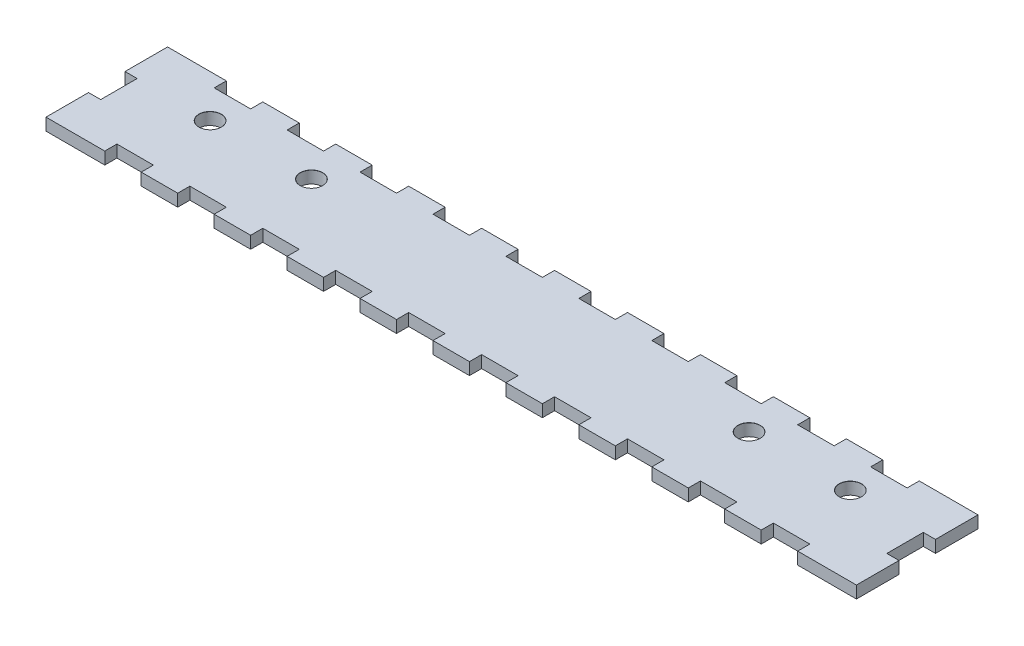
SolidWorks part; units mm, degrees
ref_plane "Front Plane" through (0, 0, 0) normal (0, 0, 1) x (1, 0, 0)
ref_plane "Top Plane" through (0, 0, 0) normal (0, 1, 0) x (1, 0, 0)
ref_plane "Right Plane" through (0, 0, 0) normal (1, 0, 0) x (0, 0, -1)
sketch "Sketch1" plane through (0, 0, 0) normal (0, 1, 0) x (1, 0, 0)
  line L0 (100, 15) -> (97, 15)
  line L1 (97, 15) -> (85.5, 15)
  line L2 (85.5, 15) -> (85.5, 12)
  line L3 (85.5, 12) -> (76.5, 12)
  line L4 (76.5, 12) -> (76.5, 15)
  line L5 (76.5, 15) -> (67.5, 15)
  line L6 (67.5, 15) -> (67.5, 12)
  line L7 (67.5, 12) -> (58.5, 12)
  line L8 (58.5, 12) -> (58.5, 15)
  line L9 (58.5, 15) -> (49.5, 15)
  line L10 (49.5, 15) -> (49.5, 12)
  line L11 (49.5, 12) -> (40.5, 12)
  line L12 (40.5, 12) -> (40.5, 15)
  line L13 (40.5, 15) -> (31.5, 15)
  line L14 (31.5, 15) -> (31.5, 12)
  line L15 (31.5, 12) -> (22.5, 12)
  line L16 (22.5, 12) -> (22.5, 15)
  line L17 (22.5, 15) -> (13.5, 15)
  line L18 (13.5, 15) -> (13.5, 12)
  line L19 (13.5, 12) -> (4.5, 12)
  line L20 (4.5, 12) -> (4.5, 15)
  line L21 (4.5, 15) -> (-4.5, 15)
  line L22 (-4.5, 15) -> (-4.5, 12)
  line L23 (-4.5, 12) -> (-13.5, 12)
  line L24 (-13.5, 12) -> (-13.5, 15)
  line L25 (-13.5, 15) -> (-22.5, 15)
  line L26 (-22.5, 15) -> (-22.5, 12)
  line L27 (-22.5, 12) -> (-31.5, 12)
  line L28 (-31.5, 12) -> (-31.5, 15)
  line L29 (-31.5, 15) -> (-40.5, 15)
  line L30 (-40.5, 15) -> (-40.5, 12)
  line L31 (-40.5, 12) -> (-49.5, 12)
  line L32 (-49.5, 12) -> (-49.5, 15)
  line L33 (-49.5, 15) -> (-58.5, 15)
  line L34 (-58.5, 15) -> (-58.5, 12)
  line L35 (-58.5, 12) -> (-67.5, 12)
  line L36 (-67.5, 12) -> (-67.5, 15)
  line L37 (-67.5, 15) -> (-76.5, 15)
  line L38 (-76.5, 15) -> (-76.5, 12)
  line L39 (-76.5, 12) -> (-85.5, 12)
  line L40 (-85.5, 12) -> (-85.5, 15)
  line L41 (-85.5, 15) -> (-97, 15)
  line L42 (-97, 15) -> (-100, 15)
  line L43 (-100, 15) -> (-100, 12)
  line L44 (-100, 12) -> (-100, 4.5)
  line L45 (-100, 4.5) -> (-97, 4.5)
  line L46 (-97, 4.5) -> (-97, -4.5)
  line L47 (-97, -4.5) -> (-100, -4.5)
  line L48 (-100, -4.5) -> (-100, -12)
  line L49 (-100, -12) -> (-100, -15)
  line L50 (-100, -15) -> (-97, -15)
  line L51 (-97, -15) -> (-85.5, -15)
  line L52 (-85.5, -15) -> (-85.5, -12)
  line L53 (-85.5, -12) -> (-76.5, -12)
  line L54 (-76.5, -12) -> (-76.5, -15)
  line L55 (-76.5, -15) -> (-67.5, -15)
  line L56 (-67.5, -15) -> (-67.5, -12)
  line L57 (-67.5, -12) -> (-58.5, -12)
  line L58 (-58.5, -12) -> (-58.5, -15)
  line L59 (-58.5, -15) -> (-49.5, -15)
  line L60 (-49.5, -15) -> (-49.5, -12)
  line L61 (-49.5, -12) -> (-40.5, -12)
  line L62 (-40.5, -12) -> (-40.5, -15)
  line L63 (-40.5, -15) -> (-31.5, -15)
  line L64 (-31.5, -15) -> (-31.5, -12)
  line L65 (-31.5, -12) -> (-22.5, -12)
  line L66 (-22.5, -12) -> (-22.5, -15)
  line L67 (-22.5, -15) -> (-13.5, -15)
  line L68 (-13.5, -15) -> (-13.5, -12)
  line L69 (-13.5, -12) -> (-4.5, -12)
  line L70 (-4.5, -12) -> (-4.5, -15)
  line L71 (-4.5, -15) -> (4.5, -15)
  line L72 (4.5, -15) -> (4.5, -12)
  line L73 (4.5, -12) -> (13.5, -12)
  line L74 (13.5, -12) -> (13.5, -15)
  line L75 (13.5, -15) -> (22.5, -15)
  line L76 (22.5, -15) -> (22.5, -12)
  line L77 (22.5, -12) -> (31.5, -12)
  line L78 (31.5, -12) -> (31.5, -15)
  line L79 (31.5, -15) -> (40.5, -15)
  line L80 (40.5, -15) -> (40.5, -12)
  line L81 (40.5, -12) -> (49.5, -12)
  line L82 (49.5, -12) -> (49.5, -15)
  line L83 (49.5, -15) -> (58.5, -15)
  line L84 (58.5, -15) -> (58.5, -12)
  line L85 (58.5, -12) -> (67.5, -12)
  line L86 (67.5, -12) -> (67.5, -15)
  line L87 (67.5, -15) -> (76.5, -15)
  line L88 (76.5, -15) -> (76.5, -12)
  line L89 (76.5, -12) -> (85.5, -12)
  line L90 (85.5, -12) -> (85.5, -15)
  line L91 (85.5, -15) -> (97, -15)
  line L92 (97, -15) -> (100, -15)
  line L93 (100, -15) -> (100, -12)
  line L94 (100, -12) -> (100, -4.5)
  line L95 (100, -4.5) -> (97, -4.5)
  line L96 (97, -4.5) -> (97, 4.5)
  line L97 (97, 4.5) -> (100, 4.5)
  line L98 (100, 4.5) -> (100, 12)
  line L99 (100, 12) -> (100, 15)
  line L100 (-100, 15) -> (100, -15) construction
  point P100 (0, 0)
extrude "Boss-Extrude1" add sketch "Sketch1" along normal mid plane 3
sketch "Sketch2" plane through (0, 1.5, 0) normal (0, 1, 0) x (1, 0, 0)
  text T0 "Left/Right\r\n"
extrude "Cut-Extrude1" [suppressed] cut sketch "Sketch2" against normal blind 1
sketch "Sketch3" plane through (0, 1.5, 0) normal (0, 1, 0) x (1, 0, 0)
  line L0 (0, 41.8956) -> (0, -48.2972) construction
  line L1 (-79, 4.5) -> (-54, 4.5) construction
  line L2 (-100, 15) -> (-100, 4.5) construction
  line L3 (-67.5, 15) -> (-76.5, 15) construction
  line L4 (79, 4.5) -> (54, 4.5) construction
  point P3 (-79, 4.5)
  point P4 (-54, 4.5)
  point P9 (79, 4.5)
  point P10 (54, 4.5)
  dimension "D1" = 25
  dimension "D2" = 21
  dimension "D3" = 10.5
hole_wizard "M5 Clearance Hole1" positions "Sketch3" profile "Sketch4" hole size "M5" standard "ISO" end condition through all
sketch "Sketch4" plane through (54, 1.5, -4.5) normal (1, 0, 0) x (0, 0, 1)
  line L0 (0, 0) -> (0, 3)
  line L1 (0, 3) -> (2.75, 3)
  line L2 (2.75, 3) -> (2.75, 0.025)
  line L3 (2.75, 0.025) -> (2.775, 0)
  line L5 (2.775, 0) -> (0, 0)
  line L6 (-2.75, 0.025) -> (-2.775, 0) construction
  line L11 (0, -6.35) -> (0, 107.95) construction
  dimension "Thru Hole Dia." = 5.5
  dimension "Thru Hole Depth" = 3
  dimension "Near C'Sink Dia." = 5.55
  dimension "Near C'Sink Angle" = 90
